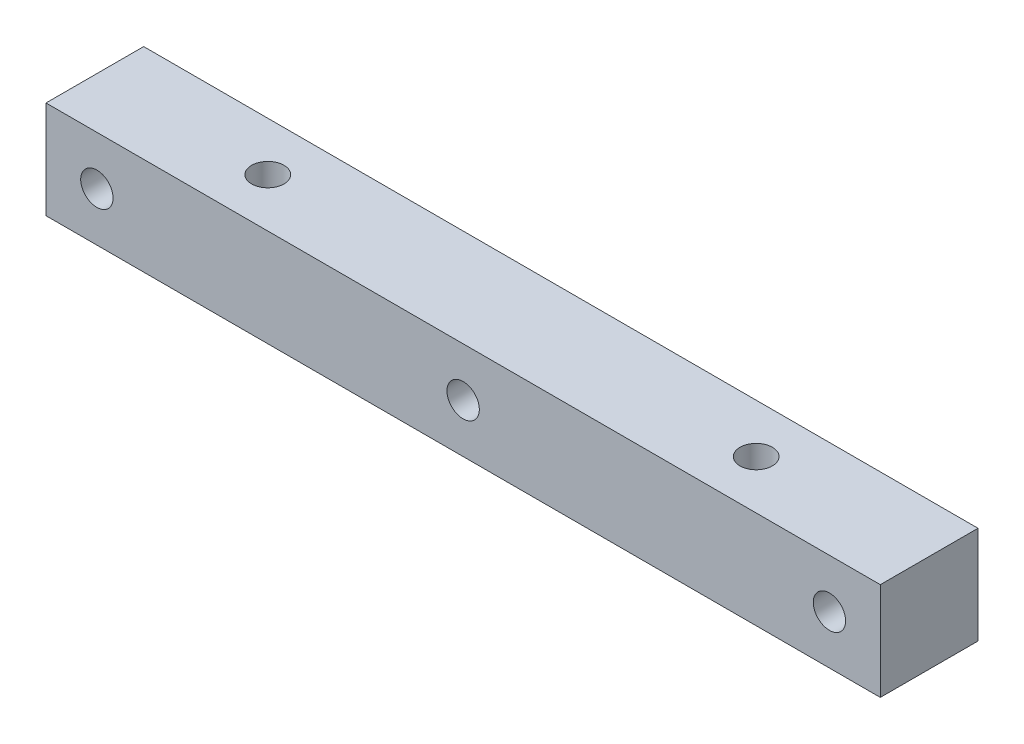
SolidWorks part; units mm, degrees
material "6061-T6 (SS)"
ref_plane "Front Plane" through (0, 0, 0) normal (0, 0, 1) x (1, 0, 0)
ref_plane "Top Plane" through (0, 0, 0) normal (0, 1, 0) x (1, 0, 0)
ref_plane "Right Plane" through (0, 0, 0) normal (1, 0, 0) x (0, 0, -1)
sketch "Sketch1" plane through (0, 0, 0) normal (1, 0, 0) x (0, -1, 0)
  line L1 (-6.096, 6.096) -> (6.096, 6.096)
  line L2 (-6.096, 6.096) -> (-6.096, -6.096)
  line L3 (-6.096, -6.096) -> (6.096, -6.096)
  line L4 (6.096, 6.096) -> (6.096, -6.096)
  line L5 (-6.096, 6.096) -> (6.096, -6.096) construction
  line L6 (-6.096, -6.096) -> (6.096, 6.096) construction
  point P0 (0, 0)
  dimension "D1" = 12.192
extrude "Boss-Extrude1" add sketch "Sketch1" along normal mid plane 104.14
sketch "Sketch2" plane through (0, 0, 6.096) normal (0, 0, 1) x (1, 0, 0)
  line L0 (-45.72, 0) -> (45.72, 0) construction
  point P3 (0, 0)
  dimension "D1" = 91.44
hole_wizard "Tap Drill for #10-32 Tap1" positions "Sketch3" profile "Sketch4" hole size "#10-32" standard "ANSI Inch" end condition through all
sketch "Sketch3" plane through (0, 0, 6.096) normal (0, 0, 1) x (1, 0, 0)
  point P0 (-45.72, 0)
  point P3 (45.72, 0)
  point P7 (0, 0)
sketch "Sketch4" plane through (-45.72, 0, 6.096) normal (1, 0, 0) x (0, -1, 0)
  line L0 (0, 0) -> (0, 12.192)
  line L1 (0, 12.192) -> (2.0193, 12.192)
  line L2 (2.0193, 12.192) -> (2.0193, 0)
  line L5 (2.0193, 0) -> (0, 0)
  line L11 (0, -6.35) -> (0, 107.95) construction
  dimension "Thru Hole Dia." = 4.0386
  dimension "Thru Hole Depth" = 12.192
sketch "Sketch5" plane through (0, 6.096, 0) normal (0, 1, 0) x (1, 0, 0)
  line L0 (-30.48, 0) -> (30.48, 0) construction
  point P3 (0, 0)
  dimension "D1" = 60.96
hole_wizard "Tap Drill for #10-32 Tap2" positions "Sketch6" profile "Sketch7" hole size "#10-32" standard "ANSI Inch" end condition through all
sketch "Sketch6" plane through (0, 6.096, 0) normal (0, 1, 0) x (1, 0, 0)
  point P0 (-30.48, 0)
  point P3 (30.48, 0)
sketch "Sketch7" plane through (-30.48, 6.096, 0) normal (1, 0, 0) x (0, 0, 1)
  line L0 (0, 0) -> (0, 12.192)
  line L1 (0, 12.192) -> (2.0193, 12.192)
  line L2 (2.0193, 12.192) -> (2.0193, 0)
  line L5 (2.0193, 0) -> (0, 0)
  line L11 (0, -6.35) -> (0, 107.95) construction
  dimension "Thru Hole Dia." = 4.0386
  dimension "Thru Hole Depth" = 12.192
